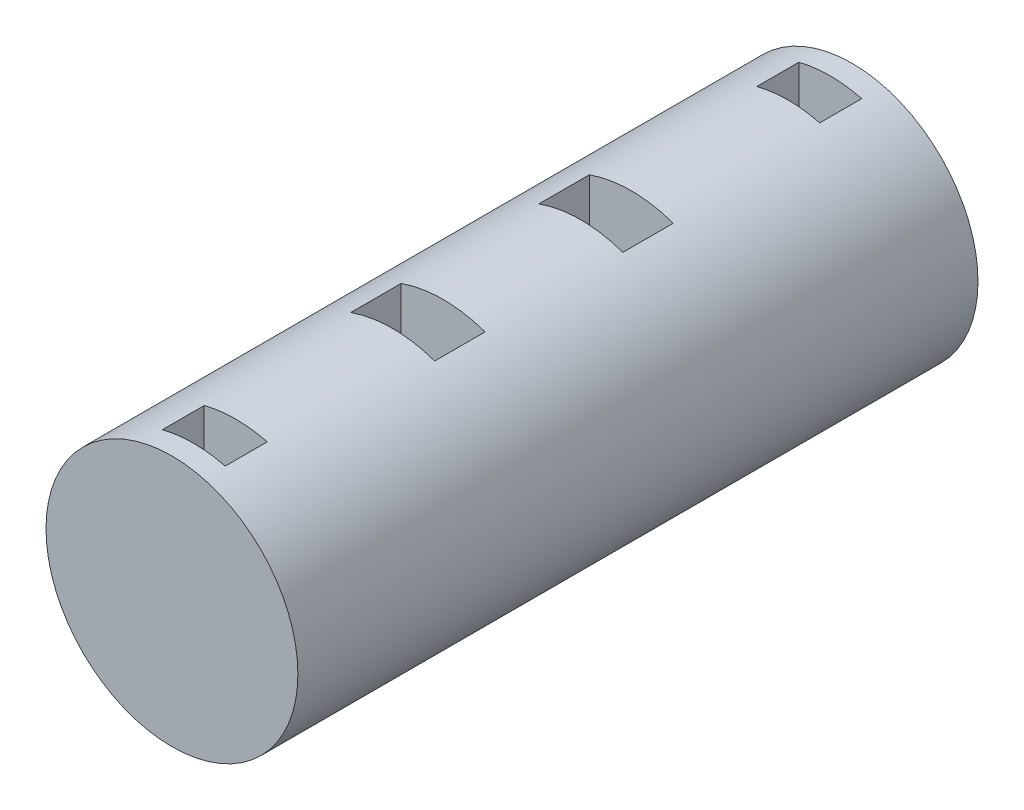
SolidWorks part; units mm, degrees
ref_plane "Front Plane" through (0, 0, 0) normal (0, 0, 1) x (1, 0, 0)
ref_plane "Top Plane" through (0, 0, 0) normal (0, 1, 0) x (1, 0, 0)
ref_plane "Right Plane" through (0, 0, 0) normal (1, 0, 0) x (0, 0, -1)
sketch "Sketch1" plane through (0, 0, 0) normal (0, 0, 1) x (1, 0, 0)
  circle A0 centre (0, 0) radius 30
extrude "Boss-Extrude6" add sketch "Sketch1" along normal blind 81
sketch "Sketch3" plane through (0, 0, 0) normal (0, 1, 0) x (1, 0, 0)
  line L0 (0, 0) -> (0, -16.4117) construction
  line L1 (0, -16.4117) -> (0, -22.4117)
  line L3 (-10, -28.4117) -> (10, -28.4117)
  line L4 (-10, -28.4117) -> (-10, -16.4117)
  line L5 (-10, -16.4117) -> (10, -16.4117)
  line L6 (10, -28.4117) -> (10, -16.4117)
  line L7 (-10, -28.4117) -> (10, -16.4117) construction
  line L8 (-10, -16.4117) -> (10, -28.4117) construction
  dimension "D1" = 20
extrude "Cut-Extrude1" cut sketch "Sketch3" against normal mid plane 81 contours L6 L5 L4 L3
sketch "Sketch4" plane through (0, 0, 0) normal (0, 1, 0) x (1, 0, 0)
  line L0 (0, -28.4117) -> (0, -70.8065) construction
  line L1 (10, -28.4117) -> (-10, -28.4117) construction
  line L3 (-7.5, -75.8065) -> (7.5, -75.8065)
  line L4 (-7.5, -75.8065) -> (-7.5, -65.8065)
  line L5 (-7.5, -65.8065) -> (7.5, -65.8065)
  line L6 (7.5, -75.8065) -> (7.5, -65.8065)
  line L7 (-7.5, -75.8065) -> (7.5, -65.8065) construction
  line L8 (-7.5, -65.8065) -> (7.5, -75.8065) construction
  point P5 (0, -70.8065)
  dimension "D1" = 10
  dimension "D2" = 15
extrude "Cut-Extrude2" cut sketch "Sketch4" against normal mid plane 81
mirror "Mirror1" about plane through (0, 0, 0) normal (0, 0, 1) of bodies 108
